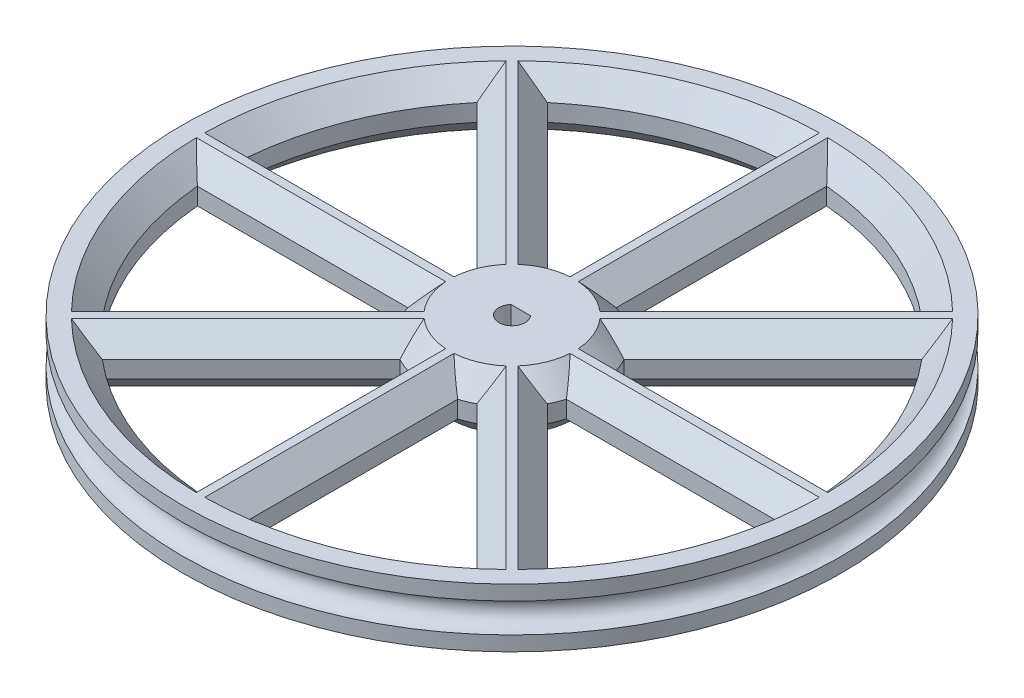
SolidWorks part; units mm, degrees
ref_plane "前视基准面" through (0, 0, 0) normal (0, 0, 1) x (1, 0, 0)
ref_plane "上视基准面" through (0, 0, 0) normal (0, 1, 0) x (1, 0, 0)
ref_plane "右视基准面" through (0, 0, 0) normal (1, 0, 0) x (0, 0, -1)
sketch "Sketch1" plane through (0, 0, 0) normal (0, 1, 0) x (1, 0, 0)
  circle A0 centre (0, 0) radius 39.6621
  dimension "D1" = 79.3242
extrude "Boss-Extrude2" add sketch "Sketch1" along normal blind 7.06
sketch "Sketch5" plane through (0, 0, 0) normal (1, 0, 0) x (0, 0, -1)
  line L0 (39.6621, 0) -> (39.6621, 7.06) construction
  circle A0 centre (39.6621, 3.53) radius 1.7653
  dimension "D1" = 3.5306
revolve "Cut-Revolve1" cut sketch "Sketch5" angle 360 about L0
sketch "Sketch7" plane through (0, 0, 0) normal (0, -1, 0) x (1, 0, 0)
  circle A0 centre (0, 0) radius 1.575
  dimension "D1" = 3.15
extrude "Cut-Extrude1" cut sketch "Sketch7" against normal blind 7.06
sketch "Sketch8" plane through (0, 0, 0) normal (0, -1, 0) x (1, 0, 0)
  line L0 (2.4188, -1.05) -> (-2.3244, -1.05) construction
  line L1 (1.1739, -1.05) -> (-1.1739, -1.05)
  arc A0 (-1.1739, -1.05) -> (1.1739, -1.05) centre (0, 0) ccw
  circle A1 centre (0, 0) radius 1.575 construction
  dimension "D1" = 1.05
extrude "Boss-Extrude4" add sketch "Sketch8" against normal blind 7.06
sketch "Sketch9" plane through (0, 7.06, 0) normal (0, 1, 0) x (1, 0, 0)
  line L0 (0, 0) -> (49.6938, 0) construction
  line L1 (0, 0) -> (-71.9649, 0) construction
  line L2 (0, 0) -> (0, -47.7178) construction
  line L3 (0, 0) -> (0, 56.442) construction
  line L4 (0, 0) -> (46.7397, 46.7397) construction
  line L5 (0, 0) -> (36.5162, -36.5162) construction
  line L6 (0, 0) -> (-48.1373, 48.1373) construction
  line L7 (0, 0) -> (-42.3978, -42.3978) construction
  line L8 (-38.9163, -43.1589) -> (59.2188, 54.9761) construction
  line L9 (-44.6354, -40.3927) -> (46.019, 50.2616) construction
  line L10 (-3, 56.442) -> (-3, -47.7178) construction
  line L11 (3, -47.7178) -> (3, 56.442) construction
  line L12 (-71.9649, 3) -> (49.6938, 3) construction
  line L13 (49.6938, -3) -> (-71.9649, -3) construction
  line L14 (-49.7206, 45.478) -> (32.3494, -36.592) construction
  line L15 (-45.3272, 49.5698) -> (38.1548, -33.9122) construction
  line L16 (-26.779, 22.5363) -> (-8.8667, 4.624)
  line L17 (-34.8712, 3) -> (-9.5394, 3)
  line L18 (-34.8712, -3) -> (-9.5394, -3)
  line L19 (-8.8667, -4.624) -> (-26.779, -22.5363)
  line L20 (-22.5363, -26.779) -> (-4.624, -8.8667)
  line L21 (-3, -9.5394) -> (-3, -34.8712)
  line L22 (3, -9.5394) -> (3, -34.8712)
  line L23 (4.624, -8.8667) -> (22.5363, -26.779)
  line L24 (8.8667, -4.624) -> (26.779, -22.5363)
  line L25 (9.5394, -3) -> (34.8712, -3)
  line L26 (9.5394, 3) -> (34.8712, 3)
  line L27 (8.8667, 4.624) -> (26.779, 22.5363)
  line L28 (3, 34.8712) -> (3, 9.5394)
  line L29 (4.624, 8.8667) -> (22.5363, 26.779)
  line L30 (-22.5363, 26.779) -> (-4.624, 8.8667)
  line L31 (-3, 34.8712) -> (-3, 9.5394)
  arc A0 (-8.8667, 4.624) -> (-9.5394, 3) centre (0, 0) ccw
  arc A1 (-26.779, 22.5363) -> (-34.8712, 3) centre (0, 0) ccw
  arc A2 (-9.5394, -3) -> (-8.8667, -4.624) centre (0, 0) ccw
  arc A3 (-34.8712, -3) -> (-26.779, -22.5363) centre (0, 0) ccw
  arc A4 (-4.624, -8.8667) -> (-3, -9.5394) centre (0, 0) ccw
  arc A5 (-22.5363, -26.779) -> (-3, -34.8712) centre (0, 0) ccw
  arc A6 (3, -34.8712) -> (22.5363, -26.779) centre (0, 0) ccw
  arc A7 (3, -9.5394) -> (4.624, -8.8667) centre (0, 0) ccw
  arc A8 (8.8667, -4.624) -> (9.5394, -3) centre (0, 0) ccw
  arc A9 (26.779, -22.5363) -> (34.8712, -3) centre (0, 0) ccw
  arc A10 (9.5394, 3) -> (8.8667, 4.624) centre (0, 0) ccw
  arc A11 (34.8712, 3) -> (26.779, 22.5363) centre (0, 0) ccw
  arc A12 (4.624, 8.8667) -> (3, 9.5394) centre (0, 0) ccw
  arc A13 (22.5363, 26.779) -> (3, 34.8712) centre (0, 0) ccw
  arc A14 (-3, 9.5394) -> (-4.624, 8.8667) centre (0, 0) ccw
  arc A15 (-3, 34.8712) -> (-22.5363, 26.779) centre (0, 0) ccw
  point P27 (-8.8667, 4.624)
  point P28 (-9.5394, 3)
  point P31 (-26.779, 22.5363)
  point P32 (-34.8712, 3)
  point P35 (-34.8712, -3)
  point P36 (-9.5394, -3)
  point P37 (-26.779, -22.5363)
  point P38 (-8.8667, -4.624)
  point P39 (-26.779, -22.5363)
  point P44 (-4.624, -8.8667)
  point P45 (-22.5363, -26.779)
  point P50 (3, -9.5394)
  point P51 (3, -34.8712)
  point P56 (8.8667, -4.624)
  point P57 (26.779, -22.5363)
  point P62 (9.5394, 3)
  point P63 (34.8712, 3)
  point P68 (4.624, 8.8667)
  point P69 (22.5363, 26.779)
  dimension "D1" = 3
  dimension "D2" = 3
  dimension "D3" = 3
  dimension "D4" = 3
  dimension "D5" = 3
  dimension "D6" = 3
  dimension "D7" = 3
  dimension "D8" = 3
  dimension "D9" = 10
  dimension "D10" = 10
  dimension "D11" = 35
  dimension "D12" = 35
  dimension "D13" = 10
  dimension "D14" = 10
  dimension "D15" = 35
  dimension "D16" = 35
  dimension "D17" = 10
  dimension "D18" = 35
  dimension "D19" = 10
  dimension "D20" = 35
  dimension "D21" = 10
  dimension "D22" = 35
extrude "Cut-Extrude2" cut sketch "Sketch9" against normal blind 7.06
chamfer "Chamfer9" distance 2.5 angle 45 2 edges at (-13.5802, 7.06, -17.8228) (-17.8228, 7.06, -13.5802)
chamfer "Chamfer10" distance 2.5 angle 45 2 edges at (-13.5802, 0, -17.8228) (-17.8228, 0, -13.5802)
chamfer "Chamfer11" distance 2.5 angle 45 30 edges at (-9.2388, 7.06, 3.8268) (-22.2053, 7.06, 3) (-32.3358, 7.06, 13.3939) (-17.8228, 7.06, 13.5802) (-3.8268, 7.06, 9.2388) (-13.5802, 7.06, 17.8228) (-13.3939, 7.06, 32.3358) (-3, 7.06, 22.2053) (13.3939, 7.06, 32.3358) (3, 7.06, 22.2053) (3.8268, 7.06, 9.2388) (13.5802, 7.06, 17.8228) (9.2388, 7.06, 3.8268) (17.8228, 7.06, 13.5802) (32.3358, 7.06, 13.3939) (22.2053, 7.06, 3) (32.3358, 7.06, -13.3939) (22.2053, 7.06, -3) (17.8228, 7.06, -13.5802) (9.2388, 7.06, -3.8268) (3.8268, 7.06, -9.2388) (13.5802, 7.06, -17.8228) (13.3939, 7.06, -32.3358) (3, 7.06, -22.2053) (-14.5417, 7.06, -31.8361) (-3, 7.06, -22.2053) (-4.9691, 7.06, -8.678) (-8.678, 7.06, -4.9691) (-22.2053, 7.06, -3) (-31.8361, 7.06, -14.5417)
chamfer "Chamfer12" distance 2.5 angle 45 30 edges at (3.8268, 0, -9.2388) (13.5802, 0, -17.8228) (13.3939, 0, -32.3358) (3, 0, -22.2053) (-14.5417, 0, -31.8361) (-4.9691, 0, -8.678) (-3, 0, -22.2053) (-8.678, 0, -4.9691) (-31.8361, 0, -14.5417) (-22.2053, 0, -3) (-17.8228, 0, 13.5802) (-9.2388, 0, 3.8268) (-32.3358, 0, 13.3939) (-22.2053, 0, 3) (-3.8268, 0, 9.2388) (-13.5802, 0, 17.8228) (-13.3939, 0, 32.3358) (-3, 0, 22.2053) (3.8268, 0, 9.2388) (3, 0, 22.2053) (13.3939, 0, 32.3358) (13.5802, 0, 17.8228) (9.2388, 0, 3.8268) (17.8228, 0, 13.5802) (32.3358, 0, 13.3939) (22.2053, 0, 3) (9.2388, 0, -3.8268) (17.8228, 0, -13.5802) (22.2053, 0, -3) (32.3358, 0, -13.3939)
